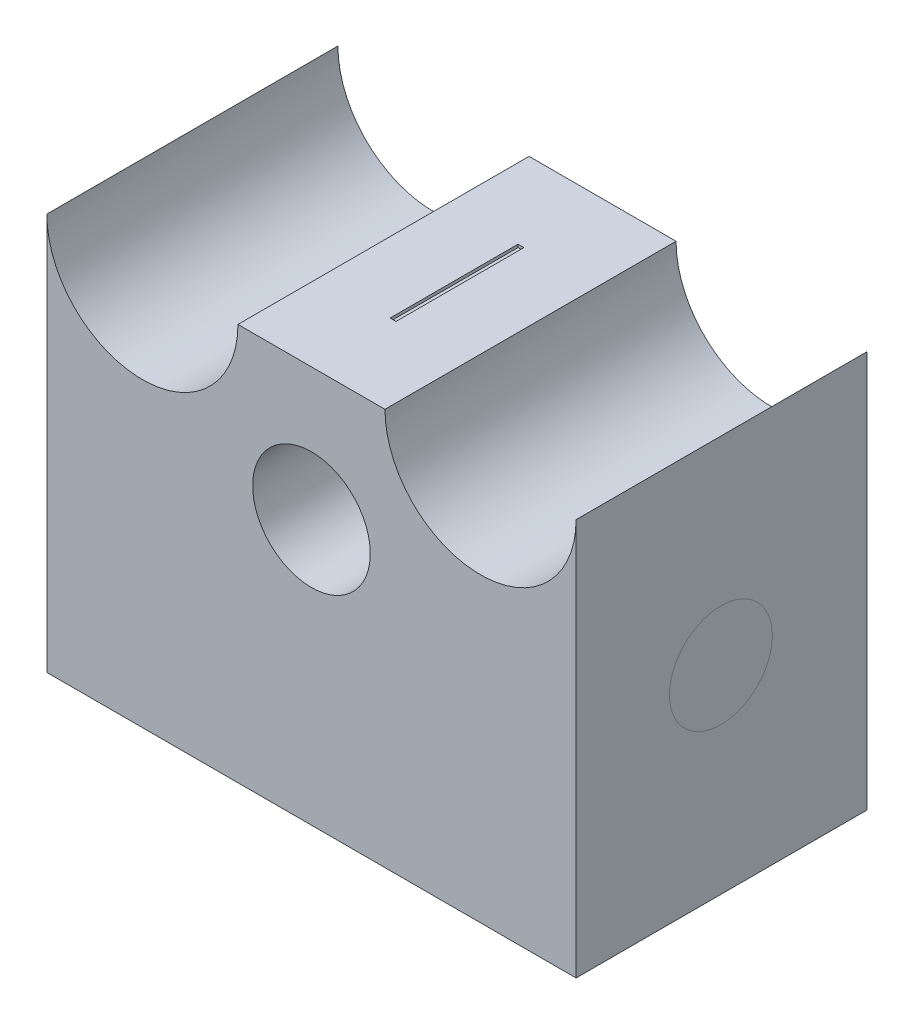
SolidWorks part; units mm, degrees
ref_plane "Front Plane" through (0, 0, 0) normal (0, 0, 1) x (1, 0, 0)
ref_plane "Top Plane" through (0, 0, 0) normal (0, 1, 0) x (1, 0, 0)
ref_plane "Right Plane" through (0, 0, 0) normal (1, 0, 0) x (0, 0, -1)
sketch "Sketch1" plane through (0, 0, 0) normal (0, 0, 1) x (1, 0, 0)
  line L1 (0, 0) -> (91.44, 0)
  line L2 (0, 0) -> (0, 68.58)
  line L3 (0, 68.58) -> (91.44, 68.58)
  line L4 (91.44, 0) -> (91.44, 68.58)
  dimension "D1" = 68.58
  dimension "D2" = 91.44
extrude "Boss-Extrude1" add sketch "Sketch1" along normal blind 50.292
sketch "Sketch2" plane through (0, 0, 50.292) normal (0, 0, 1) x (1, 0, 0)
  line L0 (91.44, 68.58) -> (0, 68.58) construction
  circle A0 centre (16.51, 68.58) radius 16.51
  circle A1 centre (74.93, 68.58) radius 16.51
  dimension "D2" = 33.02
  dimension "D4" = 33.02
  dimension "D1" = 16.51
  dimension "D3" = 16.51
extrude "Cut-Extrude1" cut sketch "Sketch2" against normal through all
sketch "Sketch3" plane through (0, 0, 50.292) normal (0, 0, 1) x (1, 0, 0)
  line L1 (91.44, 0) -> (91.44, 68.58) construction
  circle A0 centre (45.72, 45.72) radius 10.16
  dimension "D2" = 20.32
  dimension "D1" = 45.72
  dimension "D3" = 45.72
extrude "Cut-Extrude2" cut sketch "Sketch3" against normal through all
ref_plane "Plane1" through (45.72, 0, 0) normal (-1, 0, 0) x (0, 0, 1)
sketch "Sketch11" plane through (45.72, 0, 0) normal (-1, 0, 0) x (0, 0, 1)
  line L3 (0, 0) -> (33.02, 0)
  line L4 (0, 0) -> (0, 22.86)
  ellipse E0 centre (0, 0) end of major axis (-33.02, 0) minor radius 22.86 (33.02, 0) -> (0, 22.86) ccw
revolve "Cut-Revolve1" cut sketch "Sketch11" angle 360 about L3
sketch "Sketch12" plane through (0, 0, 0) normal (0, -1, 0) x (1, 0, 0)
  line L0 (71.628, 0) -> (71.12, 0)
  line L1 (20.32, 0) -> (19.812, 0)
  spline S0 degree 3 poles (-944.9342, 2803.972) (-192.2236, -264.2103) (84.0629, -90.5615) (70.3491, 9.0243) (69.8884, 11.22) (68.6746, 15.4528) (67.9215, 17.4899) (66.1439, 21.3327) (65.1194, 23.1384) (62.8263, 26.4506) (61.5577, 27.9572) (58.8108, 30.6083) (57.3323, 31.7528) (54.2122, 33.6196) (52.5702, 34.3415) (-15.8542, 54.001) (-155.5536, -297.3577) (2483.1501, -1671.7548) knots -5.317316 -5.317316 -5.317316 -5.317316 0.125 0.125 0.25 0.25 0.375 0.375 0.5 0.5 0.625 0.625 0.75 0.75 0.875 0.875 5.813789 5.813789 5.813789 5.813789 only from (71.12, 0) to (45.72, 35.56)
  spline S1 degree 3 poles (-2391.6964, -1671.7476) (246.9931, -297.3565) (107.2941, 54.001) (38.8698, 34.3415) (37.2278, 33.6196) (34.1077, 31.7528) (32.6292, 30.6083) (29.8823, 27.9572) (28.6137, 26.4506) (26.3206, 23.1384) (25.2961, 21.3327) (23.5185, 17.4899) (22.7654, 15.4528) (21.5516, 11.22) (21.0909, 9.0243) (7.3773, -90.5601) (283.6557, -264.2054) (1036.342, 2803.8408) knots -4.81378 -4.81378 -4.81378 -4.81378 0.125 0.125 0.25 0.25 0.375 0.375 0.5 0.5 0.625 0.625 0.75 0.75 0.875 0.875 6.317238 6.317238 6.317238 6.317238 only from (45.72, 35.56) to (20.32, 0)
  spline S2 degree 3 poles (71.12, 0) (71.12, 2.2762) (70.9649, 4.5524) (70.3491, 9.0243) (69.8884, 11.22) (68.6746, 15.4528) (67.9215, 17.4899) (66.1439, 21.3327) (65.1194, 23.1384) (62.8263, 26.4506) (61.5577, 27.9572) (58.8108, 30.6083) (57.3323, 31.7528) (54.2122, 33.6196) (52.5702, 34.3415) (49.1921, 35.3121) (47.4563, 35.56) (45.72, 35.56) knots 0 0 0 0 0.125 0.125 0.25 0.25 0.375 0.375 0.5 0.5 0.625 0.625 0.75 0.75 0.875 0.875 1 1 1 1
  spline S3 degree 3 poles (45.72, 35.56) (43.9837, 35.56) (42.2479, 35.3121) (38.8698, 34.3415) (37.2278, 33.6196) (34.1077, 31.7528) (32.6292, 30.6083) (29.8823, 27.9572) (28.6137, 26.4506) (26.3206, 23.1384) (25.2961, 21.3327) (23.5185, 17.4899) (22.7654, 15.4528) (21.5516, 11.22) (21.0909, 9.0243) (20.4751, 4.5524) (20.32, 2.2762) (20.32, 0) knots 0 0 0 0 0.125 0.125 0.25 0.25 0.375 0.375 0.5 0.5 0.625 0.625 0.75 0.75 0.875 0.875 1 1 1 1
  spline S4 degree 1 poles (71.628, 0) (45.72, 36.068) knots 0 0 1 1 construction
  spline S5 degree 1 poles (45.72, 36.068) (19.812, 0) knots 0 0 1 1 construction
  spline S6 degree 3 poles (71.628, 0) (71.628, 2.2912) (71.3146, 6.9012) (69.4529, 15.7732) (64.8978, 25.6811) (56.388, 33.9855) (49.2952, 36.068) (45.72, 36.068) knots 0 0 0 0 0.125 0.25 0.5 0.75 1 1 1 1
  spline S7 degree 3 poles (45.72, 36.068) (42.1448, 36.068) (35.052, 33.9855) (26.5422, 25.6811) (21.9871, 15.7732) (20.1254, 6.9012) (19.812, 2.2912) (19.812, 0) knots 0 0 0 0 0.25 0.5 0.75 0.875 1 1 1 1
  dimension "D1" = 2.54
  dimension "D2" = 0.508
sketch "Sketch15" plane through (0, 68.58, 0) normal (0, 1, 0) x (1, 0, 0)
  line L0 (46.228, -14.097) -> (46.228, -36.195)
  line L2 (91.44, -50.292) -> (91.44, 0) construction
  line L5 (58.42, 0) -> (33.02, 0) construction
  line L6 (46.228, -36.195) -> (45.212, -36.195)
  line L7 (45.212, -36.195) -> (45.212, -14.097)
  line L8 (45.212, -14.097) -> (46.228, -14.097)
  point P4 (46.228, -25.146)
  dimension "D1" = 45.212
  dimension "D2" = 25.146
  dimension "D3" = 1.016
extrude "Cut-Extrude4" cut sketch "Sketch15" against normal blind 0.508
sketch "Sketch16" plane through (91.44, 0, 0) normal (1, 0, 0) x (0, 0, -1)
  line L0 (-50.292, 0) -> (-50.292, 68.58) construction
  circle A0 centre (-25.273, 34.29) radius 8.89
  dimension "D1" = 25.019
sketch "Sketch17" plane through (0, 0, 0) normal (-1, 0, 0) x (0, 0, 1)
  circle A0 centre (25.273, 34.29) radius 8.89
split "Split1" trim tools "Sketch17" bodies to split 108 resulting bodies 105 106
extrude "Cut-Extrude3" cut sketch "Sketch12" against normal blind 0.508
